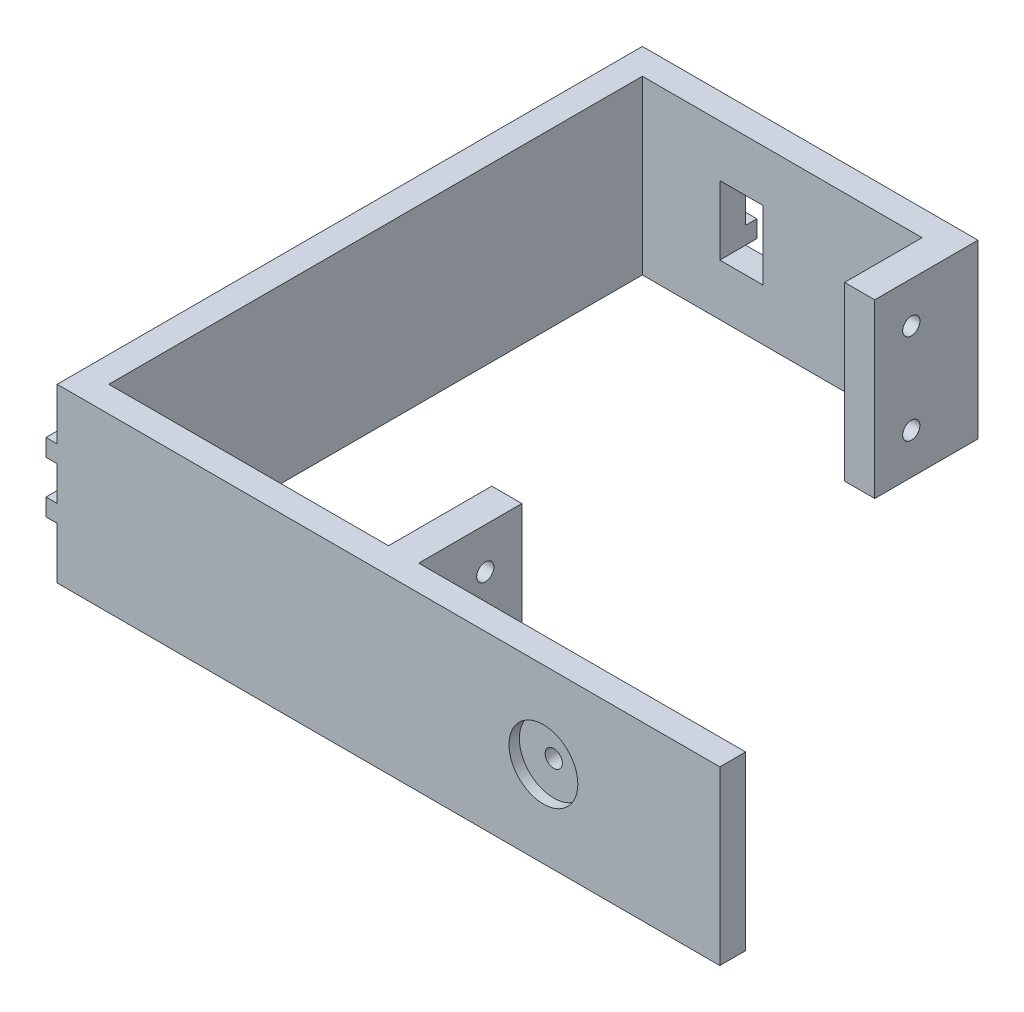
SolidWorks part; units mm, degrees
ref_plane "Alzado" through (0, 0, 0) normal (0, 0, 1) x (1, 0, 0)
ref_plane "Planta" through (0, 0, 0) normal (0, 1, 0) x (1, 0, 0)
ref_plane "Vista lateral" through (0, 0, 0) normal (1, 0, 0) x (0, 0, -1)
sketch "Croquis1" plane through (0, 0, 0) normal (0, 1, 0) x (1, 0, 0)
  line L0 (24.7296, -41.4142) -> (-52.2704, -41.4142)
  line L1 (-52.2704, -41.4142) -> (-52.2704, 26.5858)
  line L2 (-52.2704, 26.5858) -> (-13.2704, 26.5858)
  line L3 (-13.2704, 26.5858) -> (-13.2704, 14.5858)
  line L4 (-13.2704, 14.5858) -> (-16.7704, 14.5858)
  line L5 (-16.7704, 14.5858) -> (-16.7704, 23.5858)
  line L6 (-16.7704, 23.5858) -> (-49.2704, 23.5858)
  line L7 (-49.2704, 23.5858) -> (-49.2704, -38.4142)
  line L8 (-49.2704, -38.4142) -> (-16.7704, -38.4142)
  line L9 (24.7296, -41.4142) -> (24.7296, -38.4142)
  line L10 (24.7296, -38.4142) -> (-13.2704, -38.4142)
  line L12 (-13.2704, -38.4142) -> (-13.2704, -26.4142)
  line L13 (-13.2704, -26.4142) -> (-16.7704, -26.4142)
  line L14 (-16.7704, -26.4142) -> (-16.7704, -38.4142)
extrude "Saliente-Extruir1" add sketch "Croquis1" along normal blind 20 contours L2 L3 L4 L5 L6 L7 L8 L14 L13 L12 L10 L9 L0 L1
sketch "Croquis2" plane through (0, 0, 41.4142) normal (0, 0, 1) x (1, 0, 0)
  line L0 (24.7296, 10) -> (4.2296, 10)
  line L1 (24.7296, 20) -> (24.7296, 0) construction
  circle A0 centre (4.2296, 10) radius 4
extrude "Cortar-Extruir1" cut sketch "Croquis2" against normal blind 1.2 contours A0
sketch "Croquis3" plane through (0, 0, 40.2142) normal (0, 0, 1) x (1, 0, 0)
  circle A0 centre (4.2296, 10) radius 1
sketch "Croquis4" plane through (-13.2704, 0, 0) normal (1, 0, 0) x (0, 0, -1)
  circle A2 centre (-30.6642, 15.25) radius 1
  circle A3 centre (-30.6642, 4.75) radius 1
extrude "Cortar-Extruir3" cut sketch "Croquis3" against normal blind 1.8 contours A0
extrude "Cortar-Extruir4" cut sketch "Croquis4" against normal blind 3.5 contours A3 | A2
sketch "Croquis7" plane through (-13.2704, 0, 0) normal (1, 0, 0) x (0, 0, -1)
  circle A0 centre (18.8358, 15.25) radius 1
  circle A1 centre (18.8358, 4.75) radius 1
extrude "Cortar-Extruir5" cut sketch "Croquis7" against normal blind 3.5
sketch "Croquis8" plane through (0, 0, -23.5858) normal (0, 0, 1) x (1, 0, 0)
  line L0 (-35.2704, 6) -> (-35.2704, 14)
  line L2 (-35.2704, 14) -> (-40.2704, 14)
  line L4 (-40.2704, 14) -> (-40.2704, 6)
  line L5 (-40.2704, 6) -> (-35.2704, 6)
extrude "Cortar-Extruir6" cut sketch "Croquis8" against normal blind 3 contours L2 L4 L5 L0
sketch "Croquis9" plane through (0, 0, -26.5858) normal (0, 0, -1) x (-1, 0, 0)
  line L0 (40.2704, 8) -> (40.2704, 6)
  line L1 (40.2704, 14) -> (40.2704, 6) construction
  line L2 (40.2704, 8) -> (52.2704, 8)
  line L3 (52.2704, 20) -> (52.2704, 0) construction
  line L5 (52.2704, 12) -> (40.2704, 12)
  line L7 (40.2704, 6) -> (52.2704, 6)
  line L8 (52.2704, 6) -> (52.2704, 8)
  line L9 (40.2704, 12) -> (40.2704, 14)
  line L10 (40.2704, 14) -> (52.2704, 14)
  line L11 (52.2704, 14) -> (52.2704, 12)
extrude "Saliente-Extruir2" add sketch "Croquis9" along normal blind 1.3 contours L2 L8 L7 L0 | L10 L11 L5 L9
sketch "Croquis10" plane through (-52.2704, 0, 0) normal (-1, 0, 0) x (0, 0, 1)
  line L0 (-27.8858, 14) -> (41.4142, 14)
  line L1 (41.4142, 20) -> (41.4142, 0) construction
  line L2 (41.4142, 14) -> (41.4142, 12)
  line L3 (41.4142, 12) -> (-27.8858, 12)
  line L4 (-27.8858, 14) -> (-27.8858, 12) construction
  line L5 (-27.8858, 12) -> (-26.5858, 12) construction
  line L6 (-27.8858, 12) -> (-27.8858, 14)
  line L7 (-27.8858, 8) -> (41.4142, 8)
  line L8 (-27.8858, 8) -> (-27.8858, 6)
  line L9 (-27.8858, 6) -> (41.4142, 6)
  line L10 (41.4142, 6) -> (41.4142, 8)
extrude "Saliente-Extruir3" add sketch "Croquis10" along normal blind 1.3
